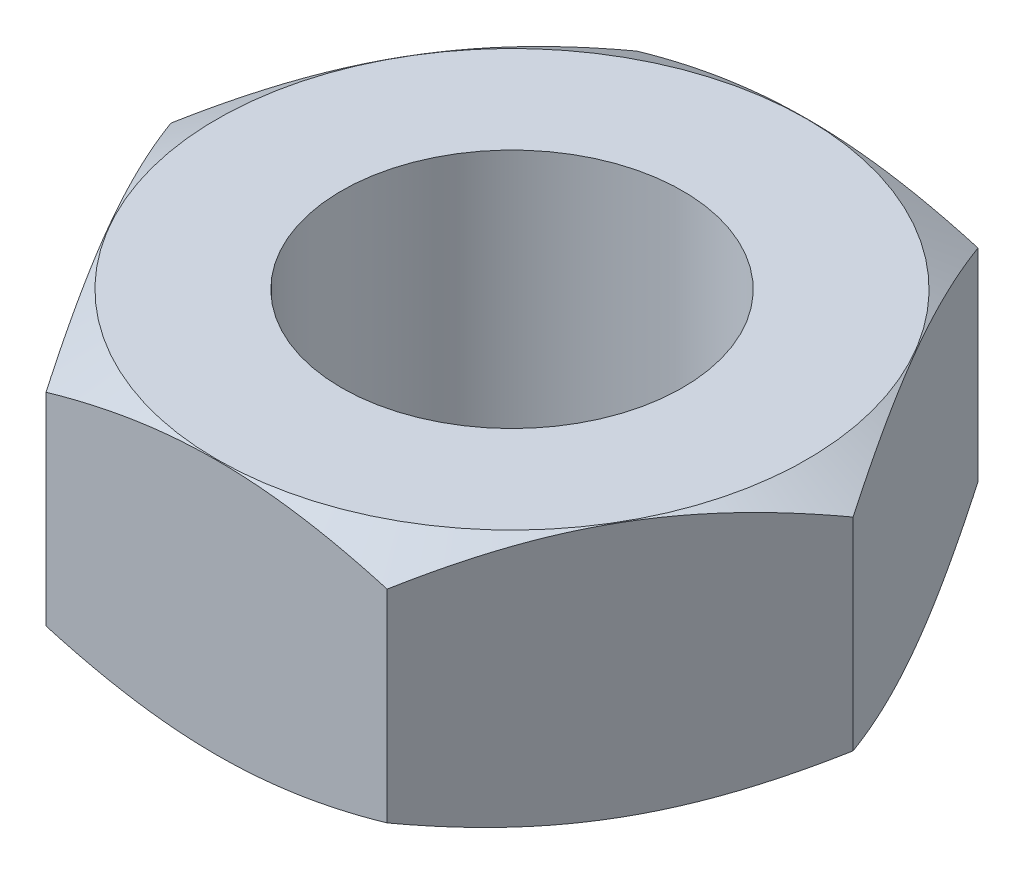
SolidWorks part; units mm, degrees
ref_plane "Front Plane" through (0, 0, 0) normal (0, 0, 1) x (1, 0, 0)
ref_plane "Top Plane" through (0, 0, 0) normal (0, 1, 0) x (1, 0, 0)
ref_plane "Right Plane" through (0, 0, 0) normal (1, 0, 0) x (0, 0, -1)
sketch "Sketch1" plane through (0, 0, 0) normal (0, 1, 0) x (1, 0, 0)
  line L1 (10, -17.3205) -> (20, 0)
  line L2 (20, 0) -> (10, 17.3205)
  line L3 (10, 17.3205) -> (-10, 17.3205)
  line L4 (-10, 17.3205) -> (-20, 0)
  line L5 (-20, 0) -> (-10, -17.3205)
  line L6 (-10, -17.3205) -> (10, -17.3205)
  circle A0 centre (0, 0) radius 17.3205 construction
  circle A1 centre (0, 0) radius 10
  dimension "D2" = 20
  dimension "D1" = 20
extrude "Boss-Extrude1" add sketch "Sketch1" along normal mid plane 15
sketch "Sketch2" plane through (0, 7.5, 0) normal (0, 1, 0) x (1, 0, 0)
  circle A0 centre (0, 0) radius 17.2911
extrude "Cut-Extrude1" cut sketch "Sketch2" against normal through all draft 60 flip side to cut
mirror "Mirror1" about plane through (0, 0, 0) normal (0, 1, 0) of "Cut-Extrude1"
